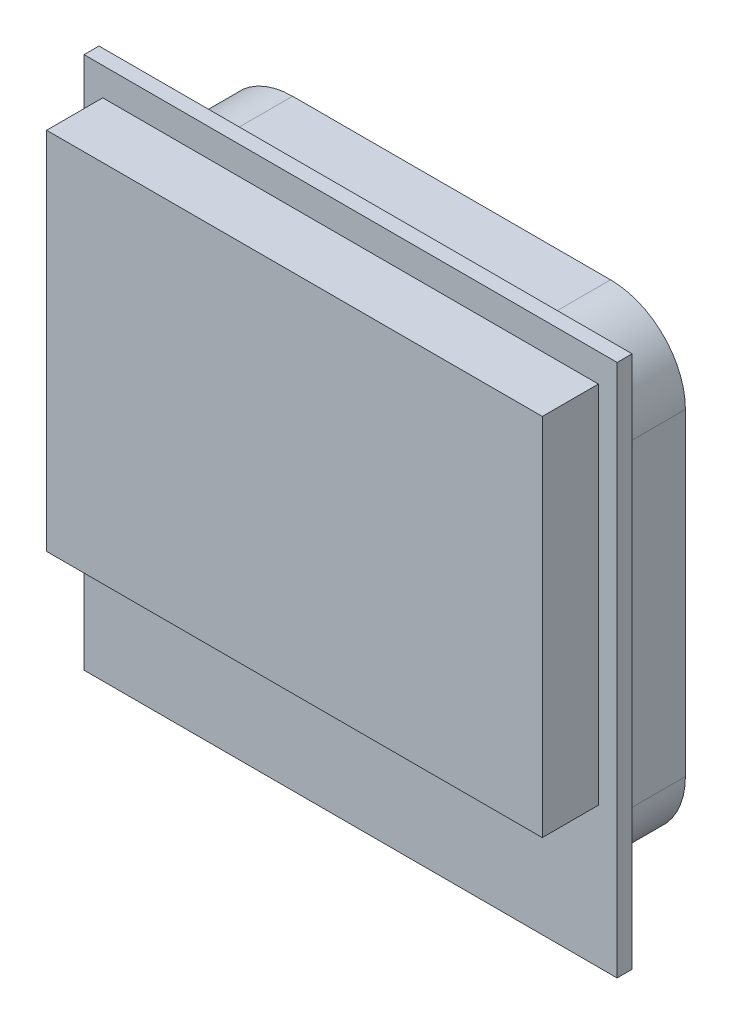
SolidWorks part; units mm, degrees
ref_plane "Спереди" through (0, 0, 0) normal (0, 0, 1) x (1, 0, 0)
ref_plane "Сверху" through (0, 0, 0) normal (0, 1, 0) x (1, 0, 0)
ref_plane "Справа" through (0, 0, 0) normal (1, 0, 0) x (0, 0, -1)
sketch "Эскиз1" plane through (0, 0, 0) normal (0, 0, 1) x (1, 0, 0)
  line L1 (-14.25, -14.25) -> (14.25, -14.25)
  line L2 (-14.25, -14.25) -> (-14.25, 14.25)
  line L3 (-14.25, 14.25) -> (14.25, 14.25)
  line L4 (14.25, -14.25) -> (14.25, 14.25)
  line L5 (-14.25, -14.25) -> (14.25, 14.25) construction
  line L6 (-14.25, 14.25) -> (14.25, -14.25) construction
  point P0 (0, 0)
  dimension "D1" = 28.5
extrude "Бобышка-Вытянуть1" add sketch "Эскиз1" along normal blind 0.8 contours L3 L4 L1 L2
sketch "Эскиз2" plane through (0, 0, 0.8) normal (0, 0, 1) x (1, 0, 0)
  line L0 (-14.25, 14.25) -> (14.25, 14.25) construction
  line L1 (-13.25, 12.75) -> (13.25, 12.75)
  line L2 (-13.25, 12.75) -> (-13.25, -6.75)
  line L3 (-13.25, -6.75) -> (13.25, -6.75)
  line L4 (13.25, 12.75) -> (13.25, -6.75)
  line L5 (-13.25, 12.75) -> (13.25, -6.75) construction
  line L6 (-13.25, -6.75) -> (13.25, 12.75) construction
  point P0 (0, 3)
  point P5 (0, 0)
  point P9 (0, 12.75)
  dimension "D1" = 26.5
  dimension "D2" = 19.5
  dimension "D3" = 0
  dimension "D4" = 1.5
extrude "Бобышка-Вытянуть2" add sketch "Эскиз2" along normal blind 3 contours L1 L4 L3 L2
sketch "Эскиз5" plane through (0, 0, 3.8) normal (0, 0, 1) x (1, 0, 0)
  line L1 (-8.5, -12.5) -> (8.5, -12.5)
  line L2 (-12.5, -8.5) -> (-12.5, 8.5)
  line L3 (-8.5, 12.5) -> (8.5, 12.5)
  line L4 (12.5, -8.5) -> (12.5, 8.5)
  line L5 (-12.5, -12.5) -> (12.5, 12.5) construction
  line L6 (-12.5, 12.5) -> (12.5, -12.5) construction
  arc A0 (8.5, -12.5) -> (12.5, -8.5) centre (8.5, -8.5) ccw
  arc A1 (-8.5, -12.5) -> (-12.5, -8.5) centre (-8.5, -8.5) cw
  arc A2 (12.5, 8.5) -> (8.5, 12.5) centre (8.5, 8.5) ccw
  arc A3 (-12.5, 8.5) -> (-8.5, 12.5) centre (-8.5, 8.5) cw
  point P0 (0, 0)
  dimension "D2" = 4
  dimension "D1" = 25
extrude "Бобышка-Вытянуть3" add sketch "Эскиз5" against normal blind 4.6 from offset 3.8 offset against normal yes
